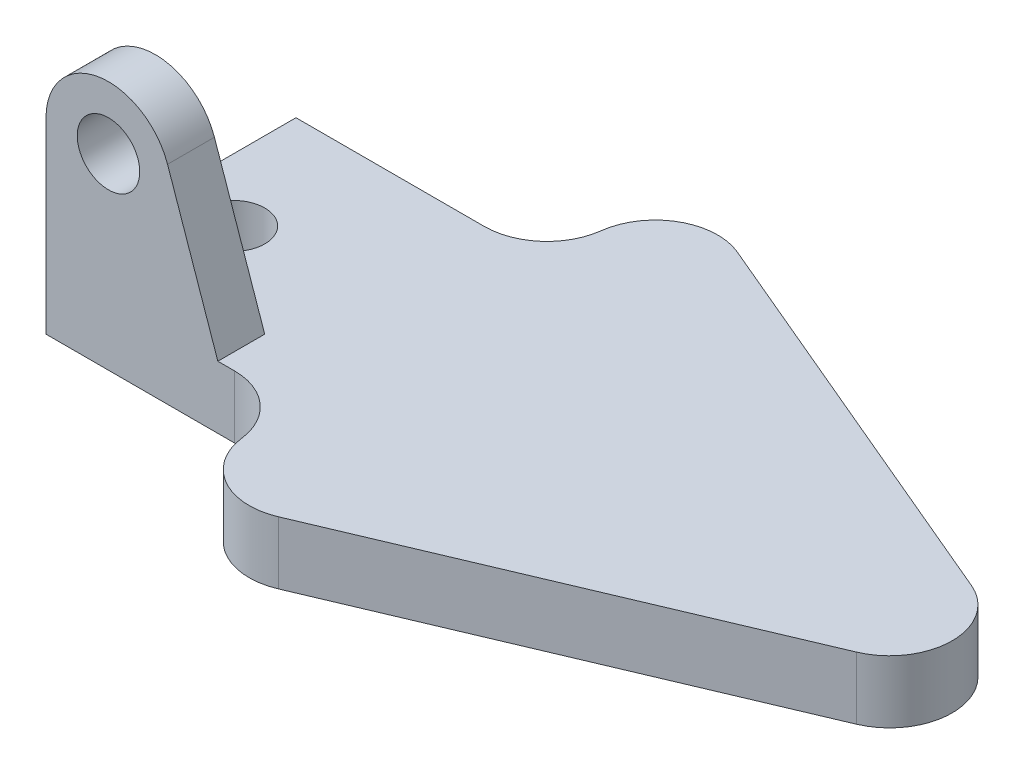
SolidWorks part; units mm, degrees
ref_plane "Front Plane" through (0, 0, 0) normal (0, 0, 1) x (1, 0, 0)
ref_plane "Top Plane" through (0, 0, 0) normal (0, 1, 0) x (1, 0, 0)
ref_plane "Right Plane" through (0, 0, 0) normal (1, 0, 0) x (0, 0, -1)
sketch "Sketch4" plane through (0, 0, 0) normal (0, 1, 0) x (1, 0, 0)
  line L0 (-77.2801, -56.6736) -> (-77.2801, 23.3264)
  line L1 (-77.2801, 23.3264) -> (-16.9664, 23.3264)
  line L2 (30.5127, 56.7457) -> (160.5127, 1.7457)
  line L3 (-77.2801, -16.6736) -> (152.7199, -16.6736) construction
  line L4 (30.5127, -90.0929) -> (160.5127, -35.0929)
  line L5 (-77.2801, -56.6736) -> (-16.9664, -56.6736)
  arc A0 (-16.9664, 23.3264) -> (2.8767, 40.8264) centre (-16.9664, 43.3264) ccw
  arc A1 (2.8767, 40.8264) -> (30.5127, 56.7457) centre (22.7199, 38.3264) cw
  arc A2 (160.5127, -35.0929) -> (160.5127, 1.7457) centre (152.7199, -16.6736) ccw
  circle A3 centre (-57.2801, -16.6736) radius 10
  arc A4 (2.8767, -74.1736) -> (30.5127, -90.0929) centre (22.7199, -71.6736) ccw
  arc A5 (-16.9664, -56.6736) -> (2.8767, -74.1736) centre (-16.9664, -76.6736) cw
  point P9 (-79.7722, -16.6736)
  point P12 (0, 0)
  point P13 (0, 0)
  point P16 (156.1036, -15.4843)
  dimension "D2" = 20
  dimension "D5" = 20
  dimension "D6" = 20
  dimension "D7" = 80
  dimension "D8" = 40
  dimension "D1" = 40
  dimension "D3" = 210
  dimension "D4" = 20
  dimension "D9" = 55
extrude "Boss-Extrude1" add sketch "Sketch4" along normal blind 20
sketch "Sketch5" plane through (0, 0, 56.6736) normal (0, 0, 1) x (1, 0, 0)
  line L0 (-77.2801, 20) -> (-77.2801, 60)
  line L1 (-38.3791, 66.5384) -> (-22.2801, 20)
  line L2 (2.8767, 20) -> (-16.9664, 20) construction
  line L3 (-77.2801, 20) -> (-22.2801, 20)
  line L4 (-77.2801, 0) -> (-16.9664, 0) construction
  arc A0 (-77.2801, 60) -> (-38.3791, 66.5384) centre (-57.2801, 60) cw
  circle A1 centre (-57.2801, 60) radius 10
  dimension "D1" = 20
  dimension "D4" = 20
  dimension "D2" = 60
  dimension "D3" = 55
extrude "Boss-Extrude2" add sketch "Sketch5" against normal blind 15
